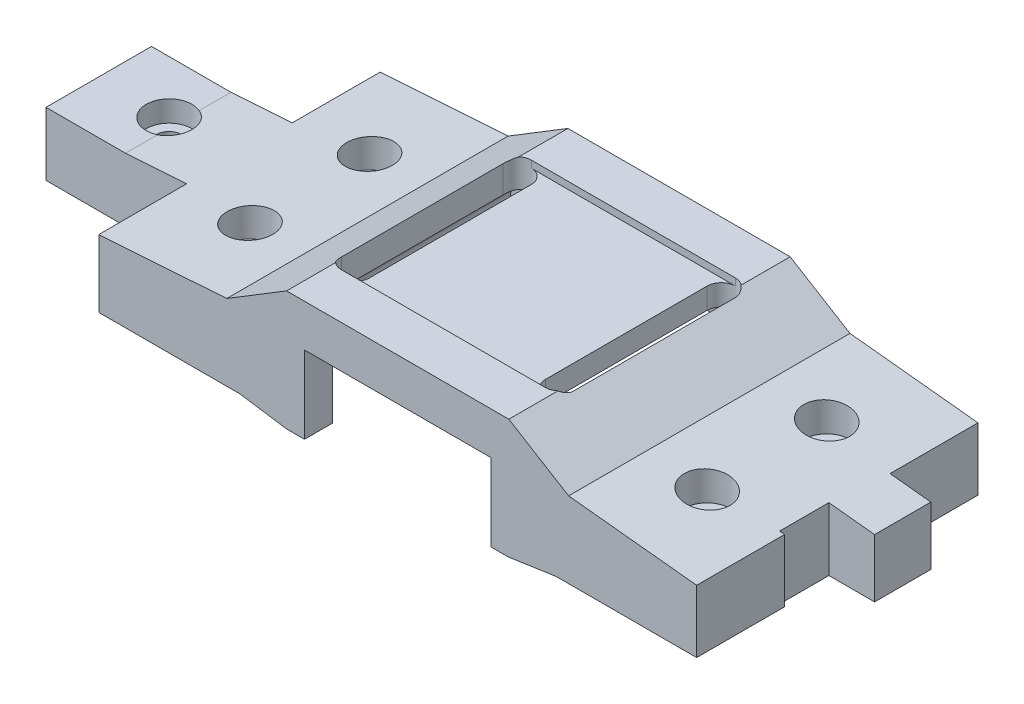
SolidWorks part; units mm, degrees
ref_plane "Front Plane" through (0, 0, 0) normal (0, 0, 1) x (1, 0, 0)
ref_plane "Top Plane" through (0, 0, 0) normal (0, 1, 0) x (1, 0, 0)
ref_plane "Right Plane" through (0, 0, 0) normal (1, 0, 0) x (0, 0, -1)
sketch "Sketch1" plane through (0, 0, 0) normal (0, 1, 0) x (1, 0, 0)
  line L0 (42.5, 20) -> (42.5, 7.5)
  line L1 (-42.5, 20) -> (42.5, 20)
  line L3 (-42.5, -20) -> (42.5, -20)
  line L5 (-42.5, 20) -> (42.5, -20) construction
  line L6 (-42.5, -20) -> (42.5, 20) construction
  line L7 (42.5, 7.5) -> (62.5, 7.5)
  line L8 (62.5, 7.5) -> (62.5, -7.5)
  line L9 (62.5, -7.5) -> (42.5, -7.5)
  line L10 (42.5, -7.5) -> (42.5, -20)
  line L11 (0, 0) -> (0, -116.996) construction
  line L12 (-42.5, -7.5) -> (-42.5, -20)
  line L13 (-62.5, -7.5) -> (-42.5, -7.5)
  line L14 (-62.5, 7.5) -> (-62.5, -7.5)
  line L15 (-42.5, 7.5) -> (-62.5, 7.5)
  line L16 (-42.5, 20) -> (-42.5, 7.5)
  circle A0 centre (-52.5, 0) radius 1.8
  circle A1 centre (-32.5, 8.5) radius 1.8
  circle A2 centre (-32.5, -8.5) radius 1.8
  circle A3 centre (32.5, -8.5) radius 1.8
  circle A4 centre (52.5, 0) radius 1.8
  circle A5 centre (32.5, 8.5) radius 1.8
  point P0 (0, 0)
  dimension "D6" = 3.6
  dimension "D1" = 85
  dimension "D2" = 40
  dimension "D3" = 20
  dimension "D4" = 15
  dimension "D5" = 12.5
  dimension "D7" = 7.5
  dimension "D8" = 10
  dimension "D9" = 10
  dimension "D10" = 1
  dimension "D11" = 10
  dimension "D12" = 1
extrude "Boss-Extrude1" add sketch "Sketch1" along normal blind 6
sketch "Sketch2" plane through (0, 0, -20) normal (0, 0, -1) x (-1, 0, 0)
  line L0 (-56, 6) -> (-40, 16)
  line L1 (-42.5, 6) -> (42.5, 6) construction
  line L2 (-40, 16) -> (40, 16)
  line L3 (40, 16) -> (56, 6)
  line L4 (-62.5, 6) -> (-42.5, 6) construction
  line L5 (-56, 6) -> (56, 6)
  dimension "D1" = 80
  dimension "D2" = 10
  dimension "D3" = 112
  dimension "D4" = 16
  dimension "D5" = 6.5
extrude "Boss-Extrude2" add sketch "Sketch2" against normal up to surface (40 mm away) up to face at (0, 3, 20)
sketch "Sketch3" plane through (0, 6, 0) normal (0, -1, 0) x (1, 0, 0)
  line L0 (-62.5, 7.5) -> (-42.5, 7.5) construction
  line L1 (-56, 20) -> (-42.5, 20)
  line L2 (-56, 20) -> (-56, 7.5)
  line L3 (-56, 7.5) -> (-42.5, 7.5)
  line L4 (-42.5, 20) -> (-42.5, 7.5)
  line L5 (-56, 7.5) -> (-42.5, 7.5) construction
  line L6 (62.5, -7.5) -> (42.5, -7.5) construction
  line L7 (-56, -7.5) -> (-42.5, -7.5)
  line L8 (-56, -7.5) -> (-56, -20)
  line L9 (-56, -20) -> (-42.5, -20)
  line L10 (-42.5, -7.5) -> (-42.5, -20)
  line L11 (42.5, -20) -> (56, -20)
  line L12 (42.5, -20) -> (42.5, -7.5)
  line L13 (42.5, -7.5) -> (56, -7.5)
  line L14 (56, -20) -> (56, -7.5)
  line L15 (56, -7.5) -> (56, -20) construction
  line L17 (56, 7.5) -> (42.5, 7.5)
  line L18 (56, 7.5) -> (56, 20)
  line L19 (56, 20) -> (42.5, 20)
  line L20 (42.5, 7.5) -> (42.5, 20)
  circle A0 centre (52.5, 0) radius 1.8 construction
  circle A1 centre (32.5, -8.5) radius 1.8 construction
  circle A2 centre (32.5, 8.5) radius 1.8 construction
  circle A3 centre (-32.5, -8.5) radius 1.8 construction
  circle A4 centre (-52.5, 0) radius 1.8 construction
  circle A5 centre (-32.5, 8.5) radius 1.8 construction
  circle A6 centre (52.5, 0) radius 1.8
  circle A7 centre (32.5, -8.5) radius 1.8
  circle A8 centre (32.5, 8.5) radius 1.8
  circle A9 centre (-32.5, -8.5) radius 1.8
  circle A10 centre (-52.5, 0) radius 1.8
  circle A11 centre (-32.5, 8.5) radius 1.8
extrude "Cut-Extrude1" cut sketch "Sketch3" against normal up to next
sketch "Sketch4" plane through (0, 16, 0) normal (0, 1, 0) x (1, 0, 0)
  circle A0 centre (-32.5, 8.5) radius 3.25
  circle A1 centre (-52.5, 0) radius 3.25
  circle A2 centre (-32.5, -8.5) radius 3.25
  circle A3 centre (32.5, 8.5) radius 3.25
  circle A4 centre (32.5, -8.5) radius 3.25
  circle A5 centre (52.5, 0) radius 3.25
  dimension "D1" = 6.5
extrude "Cut-Extrude2" cut sketch "Sketch4" against normal up to surface (10 mm away) up to face at (-59.25, 6, 0)
sketch "Sketch5" plane through (0, 0, -20) normal (0, 0, -1) x (-1, 0, 0)
  line L0 (-22.5, 0) -> (-16, 10)
  line L1 (-42.5, 0) -> (42.5, 0) construction
  line L2 (-16, 10) -> (16, 10)
  line L3 (16, 10) -> (22.5, 0)
  line L4 (22.5, 0) -> (-22.5, 0)
  dimension "D5" = 6.5
  dimension "D1" = 45
  dimension "D2" = 20
  dimension "D3" = 10
  dimension "D4" = 32
extrude "Cut-Extrude3" cut sketch "Sketch5" against normal up to next
sketch "Sketch6" plane through (0, 10, 0) normal (0, -1, 0) x (1, 0, 0)
  line L1 (-17.5, 13.5) -> (17.5, 13.5)
  line L2 (-17.5, 13.5) -> (-17.5, -13.5)
  line L3 (-17.5, -13.5) -> (17.5, -13.5)
  line L4 (17.5, 13.5) -> (17.5, -13.5)
  dimension "D1" = 27
  dimension "D2" = 13.5
  dimension "D3" = 35
  dimension "D4" = 17.5
extrude "Cut-Extrude4" cut sketch "Sketch6" against normal blind 2 and the other way up to next
fillet "Fillet1" radius 2 2 edges at (17.5, 12, 0) (-17.5, 12, 0)
sketch "Sketch7" plane through (0, 0, -20) normal (0, 0, -1) x (-1, 0, 0)
  line L0 (-22.5, 0) -> (-15.75, -1)
  line L1 (-16, 10) -> (-22.5, 0) construction
  line L2 (-15.75, -1) -> (-13.25, -1)
  line L3 (-13.25, -1) -> (-13.25, 10)
  line L4 (16, 10) -> (-16, 10) construction
  line L5 (-13.25, 10) -> (-16, 10)
  line L6 (-16, 10) -> (-22.5, 0)
  line L7 (0, 0) -> (0, -17.4167) construction
  line L8 (16, 10) -> (22.5, 0)
  line L9 (13.25, 10) -> (16, 10)
  line L10 (13.25, -1) -> (13.25, 10)
  line L11 (15.75, -1) -> (13.25, -1)
  line L12 (22.5, 0) -> (15.75, -1)
  dimension "D1" = 26.5
  dimension "D2" = 11
  dimension "D3" = 2.5
extrude "Boss-Extrude3" add sketch "Sketch7" against normal blind 4
mirror "Mirror1" about plane through (0, 0, 0) normal (0, 0, 1) of "Boss-Extrude3"
sketch "Sketch8" plane through (0, 12, 0) normal (0, -1, 0) x (1, 0, 0)
  line L0 (-14.5, 11.5) -> (-14.5, -11.5) construction
  line L1 (-12.5, 11.5) -> (-12.5, -11.5)
  line L2 (-16.5, 11.5) -> (-16.5, -11.5)
  line L3 (14.5, 11.5) -> (14.5, -11.5) construction
  line L4 (16.5, 11.5) -> (16.5, -11.5)
  line L5 (12.5, 11.5) -> (12.5, -11.5)
  arc A0 (-12.5, 11.5) -> (-16.5, 11.5) centre (-14.5, 11.5) ccw
  arc A1 (-16.5, -11.5) -> (-12.5, -11.5) centre (-14.5, -11.5) ccw
  arc A2 (16.5, 11.5) -> (12.5, 11.5) centre (14.5, 11.5) ccw
  arc A3 (12.5, -11.5) -> (16.5, -11.5) centre (14.5, -11.5) ccw
  point P2 (-14.5, 0)
  point P7 (14.5, 0)
  dimension "D1" = 2
  dimension "D2" = 2
  dimension "D3" = 29
  dimension "D4" = 14.5
  dimension "D5" = 23
  dimension "D6" = 23
extrude "Cut-Extrude5" cut sketch "Sketch8" against normal up to next and the other way up to next
sketch "Sketch9" plane through (0, 0, 16) normal (0, 0, -1) x (-1, 0, 0)
  line L1 (-13.25, 10) -> (-22.5, 10)
  line L2 (-13.25, 10) -> (-13.25, 0)
  line L3 (-13.25, 0) -> (-22.5, 0)
  line L4 (-22.5, 10) -> (-22.5, 0)
extrude "Cut-Extrude6" cut sketch "Sketch9" along normal up to surface (32 mm away) up to face at (16.15, 3.6, -16)
sketch "Sketch10" plane through (0, 16, 0) normal (0, 1, 0) x (1, 0, 0)
  line L1 (-14.5, 13.5) -> (14.5, 13.5)
  line L2 (-14.5, 13.5) -> (-14.5, -13.5)
  line L3 (-14.5, -13.5) -> (14.5, -13.5)
  line L4 (14.5, 13.5) -> (14.5, -13.5)
  arc A0 (-12.5, 11.5) -> (-16.5, 11.5) centre (-14.5, 11.5) ccw construction
  arc A1 (12.5, -11.5) -> (16.5, -11.5) centre (14.5, -11.5) ccw construction
extrude "Cut-Extrude7" cut sketch "Sketch10" against normal blind 1
sketch "Sketch11" plane through (0, 6, 0) normal (0, 1, 0) x (1, 0, 0)
  line L0 (56, 7.5) -> (42.5, 7.5) construction
  line L1 (62.5, -7.5) -> (48.3, -7.5)
  line L2 (62.5, -7.5) -> (62.5, 7.5)
  line L3 (62.5, 7.5) -> (48.3, 7.5)
  line L4 (48.3, -7.5) -> (48.3, 7.5)
  dimension "D1" = 14.2
extrude "Cut-Extrude8" cut sketch "Sketch11" against normal through all both and the other way through all
sketch "Sketch12" plane through (0, 0, 0) normal (0, -1, 0) x (1, 0, 0)
  line L0 (48.3, -7.5) -> (48.3, 7.5) construction
  line L1 (48.3, 7.5) -> (41.8, 7.5)
  line L2 (48.3, 7.5) -> (48.3, 0.5)
  line L3 (48.3, 0.5) -> (41.8, 0.5)
  line L4 (41.8, 7.5) -> (41.8, 0.5)
  point P6 (48.3, 7.4496)
  point P7 (48.3, 6.387)
  point P9 (0, 0)
  point P10 (0, 0)
  dimension "D1" = 7
  dimension "D3" = 6.5
extrude "Cut-Extrude9" cut sketch "Sketch12" against normal up to next
sketch "Sketch13" plane through (0, 0, 20) normal (0, 0, 1) x (1, 0, 0)
  line L0 (48.3, 8.2972) -> (24.3, 10.8125)
  line L1 (48.3, 10.8125) -> (48.3, 0) construction
  line L2 (24.3, 10.8125) -> (15.8, 16)
  line L3 (40, 16) -> (-40, 16) construction
  line L4 (15.8, 16) -> (-15.8, 16)
  line L5 (-15.8, 16) -> (-24.3, 10.8125)
  line L6 (-24.3, 10.8125) -> (-51.2, 9)
  line L7 (-51.2, 9) -> (-40, 16)
  line L8 (-40, 16) -> (0, 23.8284)
  line L9 (0, 23.8284) -> (40, 16)
  line L10 (40, 16) -> (48.3, 10.8125)
  line L11 (48.3, 10.8125) -> (48.3, 8.2972)
  line L12 (41.8, 0) -> (48.3, 0) construction
  line L14 (-56, 6) -> (-42.5, 14.4375) construction
  line L16 (-62.5, 6) -> (-56, 6) construction
  point P20 (0, 0)
  point P21 (-51.2159, 8.9901)
  dimension "D1" = 8.2972
  dimension "D2" = 2.5153
  dimension "D3" = 24
  dimension "D4" = 13.25
  dimension "D5" = 24.3
  dimension "D6" = 8.5
  dimension "D7" = 8.5
  dimension "D8" = 3
extrude "Cut-Extrude10" cut sketch "Sketch13" against normal up to surface (40 mm away)
sketch "Sketch14" plane through (0, 6, 0) normal (0, 1, 0) x (1, 0, 0)
  line L0 (-62.5, -7.5) -> (-56, -7.5) construction
  line L1 (-62.5, 7.5) -> (-51.2, 7.5)
  line L2 (-62.5, 7.5) -> (-62.5, -7.5)
  line L3 (-62.5, -7.5) -> (-51.2, -7.5)
  line L4 (-51.2, 2.9787) -> (-51.2, 7.5)
  line L5 (-51.2, -2.9787) -> (-51.2, -7.5)
  arc A0 (-51.2, 2.9787) -> (-51.2, -2.9787) centre (-52.5, 0) ccw
  arc A1 (-51.2, -2.9787) -> (-51.2, 2.9787) centre (-52.5, 0) ccw construction
extrude "Boss-Extrude4" add sketch "Sketch14" along normal blind 3
equation "\"D5@Sketch1\"=(\"D2@Sketch1\"-\"D4@Sketch1\")/2"
equation "\"D4@Sketch2\"=(\"D3@Sketch2\"-\"D1@Sketch2\")/2"
equation "\"D5@Sketch2\"=(125-\"D3@Sketch2\")/2"
equation "\"D2@Sketch5\"=(85-\"D1@Sketch5\")/2"
equation "\"D5@Sketch5\"=(\"D1@Sketch5\"-\"D4@Sketch5\")/2"
equation "\"D2@Sketch6\"=\"D1@Sketch6\"/2"
equation "\"D4@Sketch8\"=\"D3@Sketch8\"/2"
